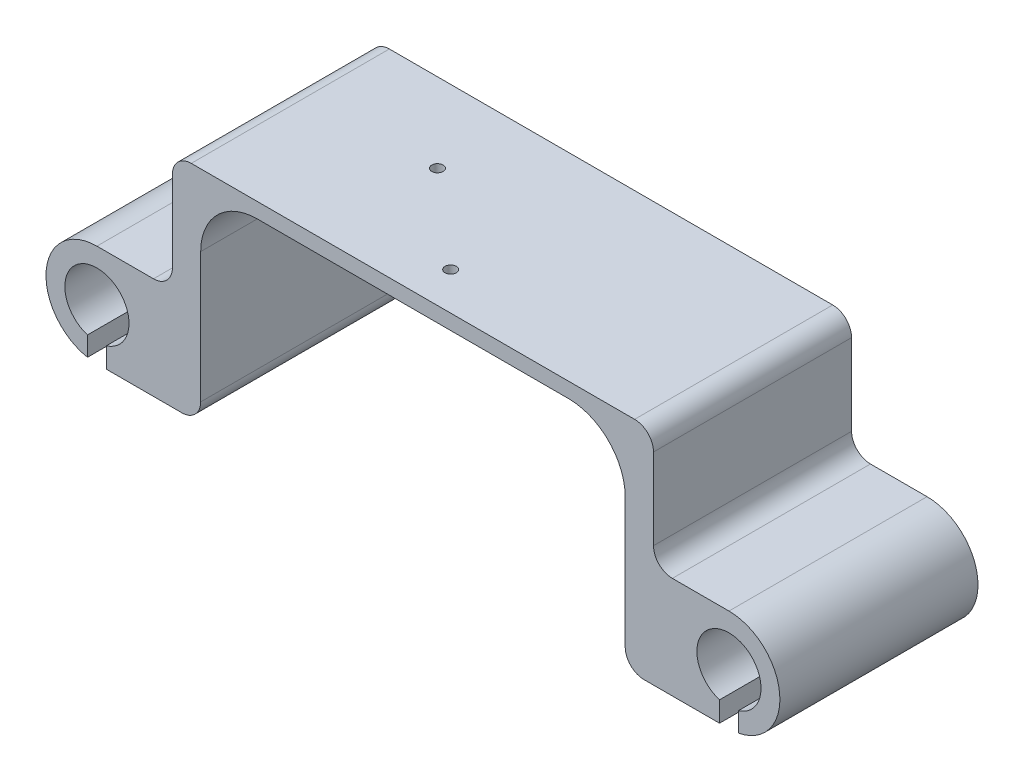
SolidWorks part; units mm, degrees
ref_plane "Front Plane" through (0, 0, 0) normal (0, 0, 1) x (1, 0, 0)
ref_plane "Top Plane" through (0, 0, 0) normal (0, 1, 0) x (1, 0, 0)
ref_plane "Right Plane" through (0, 0, 0) normal (1, 0, 0) x (0, 0, -1)
sketch "Sketch1" plane through (0, 0, 0) normal (0, 0, 1) x (1, 0, 0)
  line L0 (0, 0) -> (85.09, 0) construction
  line L3 (0, 0) -> (0, 22.86) construction
  line L5 (10.16, 22.86) -> (74.93, 22.86)
  line L7 (42.545, 22.86) -> (42.545, 19.05) construction
  line L8 (10.16, 19.05) -> (13.97, 19.05) construction
  line L9 (42.545, 19.05) -> (13.97, 19.05)
  line L10 (74.93, 19.05) -> (71.12, 19.05) construction
  line L11 (42.545, 19.05) -> (71.12, 19.05)
  line L13 (71.12, -4.572) -> (71.12, 19.05)
  line L15 (13.97, -4.572) -> (13.97, 19.05)
  line L16 (0, 6.858) -> (10.16, 6.858)
  line L17 (0, -6.858) -> (13.97, -6.858)
  line L18 (13.97, -6.858) -> (13.97, -4.572)
  line L19 (10.16, 6.858) -> (10.16, 22.86)
  line L20 (85.09, -6.858) -> (71.12, -6.858)
  line L21 (71.12, -6.858) -> (71.12, -4.572)
  line L22 (85.09, 6.858) -> (74.93, 6.858)
  line L23 (74.93, 22.86) -> (74.93, 6.858)
  circle A1 centre (0, 0) radius 1.905
  circle A2 centre (85.09, 0) radius 1.905
  arc A8 (0, -6.858) -> (0, 6.858) centre (0, 0) cw
  arc A10 (85.09, 6.858) -> (85.09, -6.858) centre (85.09, 0) cw
extrude "Boss-Extrude1" add sketch "Sketch1" against normal blind 26.67
ref_plane "Plane1" through (0, 0, 0) normal (0, 0, 1) x (1, 0, 0)
sketch "Sketch3" plane through (0, 0, 0) normal (0, 0, 1) x (1, 0, 0)
  line L0 (85.09, 0) -> (86.36, 0) construction
  line L1 (85.09, 0) -> (83.82, 0) construction
  line L2 (83.82, -4.127) -> (83.82, -6.858)
  line L4 (71.12, -6.858) -> (85.09, -6.858) construction
  line L5 (86.36, -4.127) -> (86.36, -6.7394)
  line L6 (83.82, -6.858) -> (85.09, -6.858)
  line L7 (0, 0) -> (1.27, 0) construction
  line L8 (0, 0) -> (-1.27, 0) construction
  line L9 (-1.27, -4.127) -> (-1.27, -6.7394)
  line L10 (1.27, -4.127) -> (1.27, -6.858)
  line L11 (0, -6.858) -> (13.97, -6.858) construction
  line L12 (1.27, -6.858) -> (0, -6.858)
  arc A1 (85.09, -6.858) -> (85.09, 6.858) centre (85.09, 0) ccw construction
  arc A4 (85.09, -6.858) -> (86.36, -6.7394) centre (85.09, 0) ccw
  arc A5 (86.36, -4.127) -> (83.82, -4.127) centre (85.09, 0) ccw
  arc A7 (0, 6.858) -> (0, -6.858) centre (0, 0) ccw construction
  arc A8 (-1.27, -6.7394) -> (0, -6.858) centre (0, 0) ccw
  arc A9 (1.27, -4.127) -> (-1.27, -4.127) centre (0, 0) ccw
extrude "Cut-Extrude1" cut sketch "Sketch3" against normal blind 22.86
ref_plane "Plane2" through (0, 22.86, 0) normal (0, 1, 0) x (1, 0, 0)
ref_plane "Plane3" through (0, 19.05, 0) normal (0, -1, 0) x (-1, 0, 0)
sketch "Sketch8" plane through (0, 19.05, 0) normal (0, -1, 0) x (-1, 0, 0)
  line L1 (-71.12, 26.67) -> (-13.97, 26.67)
  line L2 (-71.12, 26.67) -> (-71.12, 0)
  line L3 (-71.12, 0) -> (-13.97, 0)
  line L4 (-13.97, 26.67) -> (-13.97, 0)
extrude "Cut-Extrude4" cut sketch "Sketch8" against normal blind 1.778
ref_plane "Plane5" through (0, 20.828, 0) normal (0, -1, 0) x (-1, 0, 0)
sketch "Sketch6" plane through (0, 20.828, 0) normal (0, -1, 0) x (-1, 0, 0)
  line L0 (-42.545, 26.67) -> (-42.545, 5.08) construction
  line L1 (-13.97, 26.67) -> (-71.12, 26.67) construction
  line L2 (-42.545, 5.08) -> (-29.845, 5.08) construction
  line L4 (-29.845, 5.08) -> (-29.845, 16.002) construction
  circle A1 centre (-42.545, 5.08) radius 2.54
  circle A2 centre (-29.845, 16.002) radius 2.54
extrude "Boss-Extrude3" add sketch "Sketch6" along normal blind 2.54
ref_plane "Plane4" through (0, 18.288, 0) normal (0, -1, 0) x (-1, 0, 0)
sketch "Sketch7" plane through (0, 18.288, 0) normal (0, -1, 0) x (-1, 0, 0)
  circle A0 centre (-42.545, 5.08) radius 0.762
  circle A1 centre (-29.845, 16.002) radius 0.762
extrude "Cut-Extrude3" cut sketch "Sketch7" against normal blind 7.62
fillet "Fillet1" radius 2.54 6 edges at (74.93, 6.858, -13.335) (74.93, 22.86, -13.335) (10.16, 6.858, -13.335) (10.16, 22.86, -13.335) (13.97, -6.858, -13.335) (71.12, -6.858, -13.335)
fillet "Fillet4" radius 7.62 2 edges at (13.97, 20.828, -13.335) (71.12, 20.828, -13.335)
sketch "Sketch9" plane through (0, 20.828, 0) normal (0, -1, 0) x (-1, 0, 0)
  line L0 (-29.845, 16.002) -> (-52.705, 16.002) construction
  circle A0 centre (-52.705, 16.002) radius 2.54
extrude "Boss-Extrude4" add sketch "Sketch9" along normal blind 2.54
fillet "Fillet3" radius 1.27 3 edges at (29.845, 20.828, -18.542) (42.545, 20.828, -7.62) (52.705, 20.828, -18.542)
